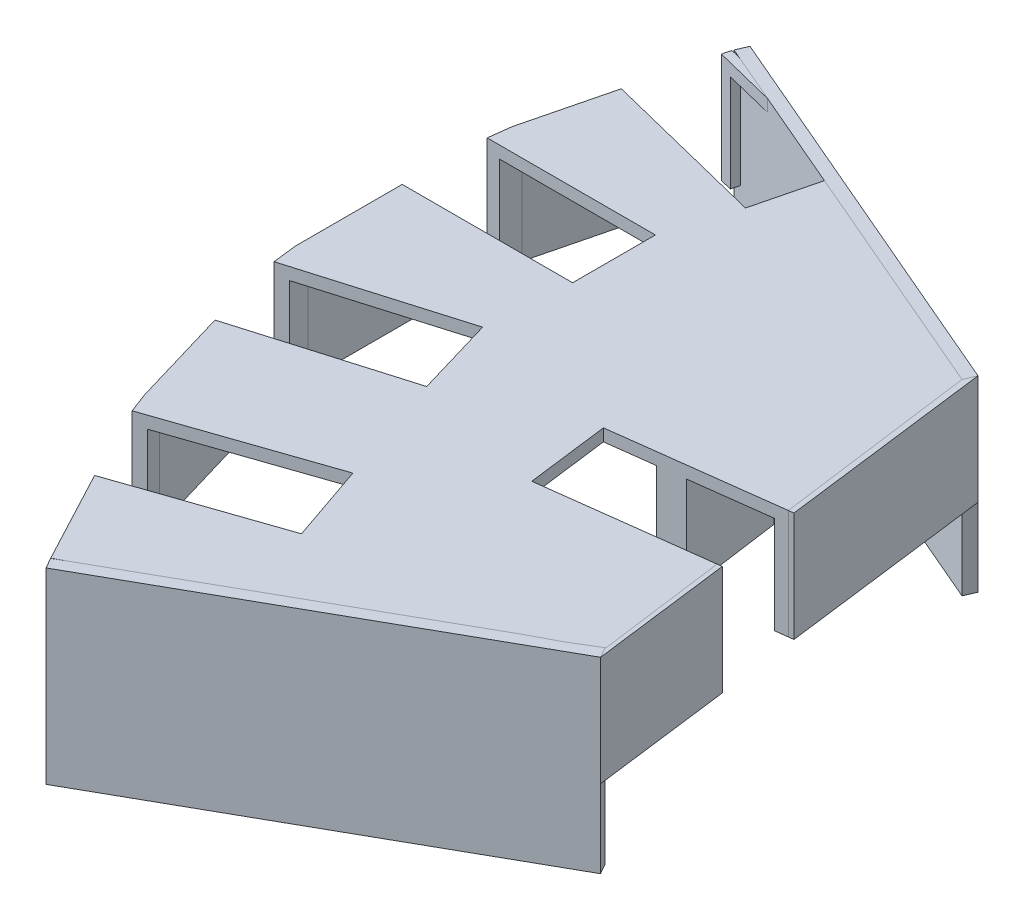
SolidWorks part; units mm, degrees
material "ABS"
ref_plane "Front Plane" through (0, 0, 0) normal (0, 0, 1) x (1, 0, 0)
ref_plane "Top Plane" through (0, 0, 0) normal (0, 1, 0) x (1, 0, 0)
ref_plane "Right Plane" through (0, 0, 0) normal (1, 0, 0) x (0, 0, -1)
sketch "Sketch1" plane through (0, 0, 0) normal (0, 1, 0) x (1, 0, 0)
  line B0 (33.1518, -28.8895) -> (43.5329, -48.4403)
  line B1 (43.5329, -48.4403) -> (55.0199, -42.3409)
  line B2 (55.0199, -42.3409) -> (43.7944, 42.3024)
  line B3 (43.7944, 42.3024) -> (30.6314, 47.9501)
  line B4 (30.6314, 47.9501) -> (24.8103, 22.9246)
  line B5 (24.8103, 22.9246) -> (25.1095, 19.3427)
  line B6 (25.1095, 19.3427) -> (25.1128, -0.6573)
  line B7 (25.1128, -0.6573) -> (25.7623, -5.3653)
  line B8 (25.7623, -5.3653) -> (31.4294, -24.5455)
  line B9 (31.4294, -24.5455) -> (33.1518, -28.8895)
  line B10 (-35.9595, 76.5212) -> (-38.3852, 77.126)
  line B11 (-38.3852, 77.126) -> (-47.3731, 41.0777)
  line B12 (-47.3731, 41.0777) -> (-48.3976, 32.789)
  line B13 (-48.3976, 32.789) -> (-48.3918, -2.5178)
  line B14 (-48.3918, -2.5178) -> (-47.3991, -10.603)
  line B15 (-47.3991, -10.603) -> (-37.3948, -44.4619)
  line B16 (-37.3948, -44.4619) -> (-34.498, -52.0083)
  line B17 (-34.498, -52.0083) -> (-18.0128, -83.0553)
  line B18 (-18.0128, -83.0553) -> (-15.8048, -81.8828)
  line B19 (-15.8048, -81.8828) -> (-32.2186, -50.9703)
  line B20 (-32.2186, -50.9703) -> (-35.0254, -43.6585)
  line B21 (-35.0254, -43.6585) -> (-44.9429, -10.093)
  line B22 (-44.9429, -10.093) -> (-45.8919, -2.3647)
  line B23 (-45.8919, -2.3647) -> (-45.8976, 32.6353)
  line B24 (-45.8976, 32.6353) -> (-44.9106, 40.6202)
  line B25 (-44.9106, 40.6202) -> (-35.9595, 76.5212)
  line B26 (32.3898, 44.4752) -> (27.3343, 22.741)
  line B27 (27.3343, 22.741) -> (43.5675, 24.9979)
  line B28 (43.5675, 24.9979) -> (41.5029, 40.5652)
  line B29 (41.5029, 40.5652) -> (32.3898, 44.4752)
  line B30 (27.7474, 19.7696) -> (33.795, -23.729)
  line B31 (33.795, -23.729) -> (35.4248, -27.8394)
  line B32 (35.4248, -27.8394) -> (44.5685, -45.0598)
  line B33 (44.5685, -45.0598) -> (52.3132, -40.9476)
  line B34 (52.3132, -40.9476) -> (43.9619, 22.0239)
  line B35 (43.9619, 22.0239) -> (27.7474, 19.7696)
sketch_block_instance "upper cover-1"
sketch_block "upper cover"
extrude "Boss-Extrude1" add sketch "Sketch1" along normal blind 20
sketch "Sketch5" plane through (0, 20, 0) normal (0, 1, 0) x (1, 0, 0)
  line L0 (-15.8048, -81.8828) -> (43.5329, -48.4403)
  line L1 (43.5329, -48.4403) -> (55.0199, -42.3409)
  line L2 (55.0199, -42.3409) -> (43.7944, 42.3024)
  line L3 (43.7944, 42.3024) -> (30.6314, 47.9501)
  line L4 (30.6314, 47.9501) -> (-35.9595, 76.5212)
  line L5 (-38.3852, 77.126) -> (-47.3731, 41.0777)
  line L6 (-47.3731, 41.0777) -> (-48.3976, 32.789)
  line L7 (-48.3976, 32.789) -> (-48.3918, -2.5178)
  line L8 (-48.3918, -2.5178) -> (-47.3991, -10.603)
  line L9 (-47.3991, -10.603) -> (-37.3948, -44.4619)
  line L10 (-37.3948, -44.4619) -> (-34.498, -52.0083)
  line L11 (-34.498, -52.0083) -> (-18.0128, -83.0553)
  line L12 (-18.0128, -83.0553) -> (-15.8048, -81.8828)
  arc A0 (-35.9595, 76.5212) -> (-38.3852, 77.126) centre (-39.0349, 69.3532) ccw
extrude "Boss-Extrude3" add sketch "Sketch5" along normal blind 2.5
sketch "Sketch6" plane through (31.2139, 0, 55.3832) normal (0.491, 0, 0.8712) x (0.8712, 0, -0.491)
  line L0 (-53.972, 22.5) -> (14.1408, 22.5)
  line L1 (14.1408, 22.5) -> (27.1426, 22.5)
  line L2 (27.1426, 22.5) -> (27.1426, 0)
  line L5 (-56.4712, 0) -> (-56.4712, 22.5)
  line L6 (-56.4712, 22.5) -> (-53.972, 22.5)
  line L7 (-56.4712, 0) -> (-56.4712, -16)
  line L8 (-56.4712, -16) -> (27.1426, -16)
  line L9 (27.1426, -16) -> (27.1426, 0)
  dimension "D1" = 16
extrude "Boss-Extrude5" add sketch "Sketch6" along normal blind 2.5 separate body
sketch "Sketch7" plane through (22.1369, 0, -51.5946) normal (0.3943, 0, -0.919) x (-0.919, 0, -0.3943)
  line L0 (-23.5668, 0) -> (-23.5668, 22.5)
  line L1 (-23.5668, 22.5) -> (65.6858, 22.5)
  line L2 (65.6858, 22.5) -> (65.6858, 0)
  line L4 (-23.5668, 0) -> (-23.5668, -16)
  line L5 (-16.2446, -16) -> (-66.9978, -16) construction
  line L6 (-23.5668, -16) -> (65.6858, -16)
  line L7 (65.6858, -16) -> (65.6858, 0)
extrude "Boss-Extrude7" add sketch "Sketch7" along normal blind 2.5 separate body
sketch "Sketch8" plane through (0, 0, 0) normal (0, -1, 0) x (1, 0, 0)
  line L0 (56.0871, 44.2345) -> (44.7802, -44.5999)
  line L1 (44.7802, -44.5999) -> (43.7944, -42.3024)
  line L2 (43.7944, -42.3024) -> (55.0199, 42.3409)
  line L3 (55.0199, 42.3409) -> (56.0871, 44.2345)
extrude "Boss-Extrude9" add sketch "Sketch8" against normal up to surface (22.5 mm away) separate body up to face at (-17.6343, 22.5, 7.3382)
extrude "Cut-Extrude1" cut sketch "Sketch9" against normal blind 35
sketch "Sketch9" plane through (-42.8219, 22.5, -75.4629) normal (0, 1, 0) x (0.9989, 0, -0.0477)
  line L1 (0.746, -124.24) -> (35.3124, -114.1821)
  line L2 (0.746, -124.24) -> (5.4956, -140.563)
  line L3 (5.4956, -140.563) -> (40.062, -130.5051)
  line L4 (35.3124, -114.1821) -> (40.062, -130.5051)
  point P4 (0, 0)
  point P5 (8.159, -142.934)
extrude "Cut-Extrude2" cut sketch "Sketch10" against normal blind 30
sketch "Sketch10" plane through (-45.1481, 22.5, -78.2938) normal (0, 1, 0) x (0.9991, 0, -0.0435)
  line L0 (-6.8864, -85.6229) -> (27.0788, -77.1754)
  line L1 (27.0788, -77.1754) -> (31.1819, -93.6729)
  line L2 (31.1819, -93.6729) -> (-2.7834, -102.1203)
  line L3 (-2.7834, -102.1203) -> (-6.8864, -85.6229)
extrude "Cut-Extrude3" cut sketch "Sketch11" against normal blind 35
sketch "Sketch11" plane through (-42.8219, 22.5, -75.4629) normal (0, 1, 0) x (0.9989, 0, -0.0477)
  line L6 (-5.397, -99.1626) -> (28.603, -90.8561)
  line L7 (28.603, -90.8561) -> (24.5684, -74.3418)
  line L8 (24.5684, -74.3418) -> (-9.4316, -82.6483)
  line L9 (-9.4316, -82.6483) -> (-5.397, -99.1626)
extrude "Cut-Extrude5" cut sketch "Sketch13" against normal blind 35
sketch "Sketch13" plane through (-42.8219, 22.5, -75.4629) normal (0, 1, 0) x (0.9989, 0, -0.0477)
  line L0 (-7.4266, -38.6458) -> (27.5339, -40.3081)
  line L1 (27.5339, -40.3081) -> (26.7265, -57.2889)
  line L2 (26.7265, -57.2889) -> (-8.234, -55.6266)
  line L3 (-8.234, -55.6266) -> (-7.4266, -38.6458)
extrude "Cut-Extrude7" cut sketch "Sketch15" against normal blind 35
sketch "Sketch15" plane through (-42.8219, 22.5, -75.4629) normal (0, 1, 0) x (0.9989, 0, -0.0477)
  line L0 (4.0201, -0.1828) -> (16.4697, -3.9254)
  line L1 (36.51, -13.6796) -> (32.6594, -26.4886)
  line L2 (32.6594, -26.4886) -> (-0.8588, -16.4125)
  line L3 (-0.8588, -16.4125) -> (4.0201, -0.1828)
  line L5 (16.4697, -3.9254) -> (36.51, -13.6796)
extrude "Cut-Extrude8" cut sketch "Sketch16" against normal blind 35
sketch "Sketch16" plane through (-42.8219, 22.5, -75.4629) normal (0, 1, 0) x (0.9989, 0, -0.0477)
  line L0 (54.5823, -81.2812) -> (89.4734, -78.5217)
  line L1 (89.4734, -78.5217) -> (90.8136, -95.4688)
  line L2 (90.8136, -95.4688) -> (55.9226, -98.2282)
  line L3 (55.9226, -98.2282) -> (54.5823, -81.2812)
